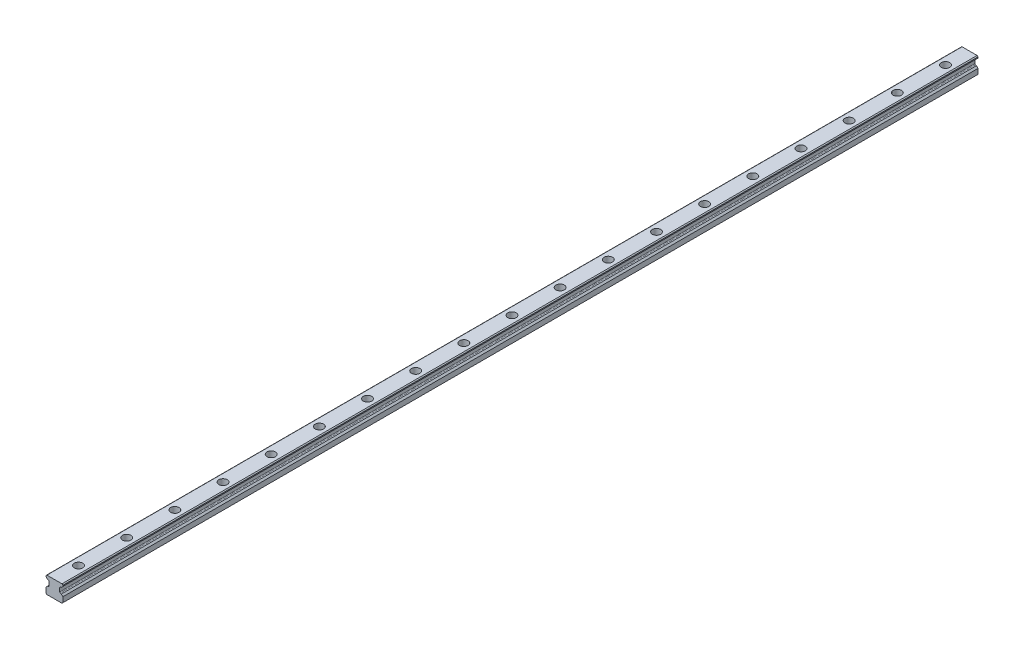
SolidWorks part; units mm, degrees
ref_plane "Front" through (0, 0, 0) normal (0, 0, 1) x (1, 0, 0)
ref_plane "Top" through (0, 0, 0) normal (0, 1, 0) x (1, 0, 0)
ref_plane "Right" through (0, 0, 0) normal (1, 0, 0) x (0, 0, -1)
sketch "Sketch1" plane through (0, 0, 0) normal (0, 0, 1) x (1, 0, 0)
  line L36 (-9.9118, 13.1068) -> (-11.43, 12.7)
  line L37 (-11.43, 12.7) -> (-14, 10.13)
  line L38 (-14, 10.13) -> (-14, 1.5)
  line L39 (-14, 1.5) -> (-12.5, 0)
  line L40 (-12.5, 0) -> (12.5, 0)
  line L41 (12.5, 0) -> (14, 1.5)
  line L42 (14, 1.5) -> (14, 10.13)
  line L43 (14, 10.13) -> (11.43, 12.7)
  line L44 (11.43, 12.7) -> (9.9118, 13.1068)
  line L45 (8.8, 14.5557) -> (8.8, 20.4443)
  line L46 (9.9118, 21.8932) -> (11.43, 22.3)
  line L47 (11.43, 22.3) -> (14, 24.87)
  line L48 (14, 24.87) -> (14, 26.5)
  line L49 (12.5, 28) -> (-12.5, 28)
  line L50 (-14, 26.5) -> (-14, 24.87)
  line L51 (-14, 24.87) -> (-11.43, 22.3)
  line L52 (-11.43, 22.3) -> (-9.9118, 21.8932)
  line L53 (-8.8, 20.4443) -> (-8.8, 14.5557)
  arc A12 (8.8, 14.5557) -> (9.9118, 13.1068) centre (10.3, 14.5557) ccw
  arc A13 (9.9118, 21.8932) -> (8.8, 20.4443) centre (10.3, 20.4443) ccw
  arc A14 (14, 26.5) -> (12.5, 28) centre (11.6492, 25.6492) ccw
  arc A15 (-12.5, 28) -> (-14, 26.5) centre (-11.6492, 25.6492) ccw
  arc A16 (-8.8, 20.4443) -> (-9.9118, 21.8932) centre (-10.3, 20.4443) ccw
  arc A17 (-9.9118, 13.1068) -> (-8.8, 14.5557) centre (-10.3, 14.5557) ccw
extrude "Boss-Extrude1" add sketch "Sketch1" along normal mid plane 1520
sketch "Sketch2" plane through (0, 0, 0) normal (1, 0, 0) x (0, 0, -1)
  line L0 (-720, 28) -> (-720, 0) construction
  line L3 (-720, 28) -> (-713, 28)
  line L4 (-713, 28) -> (-713, 16)
  line L5 (-713, 16) -> (-715.5, 16)
  line L6 (-715.5, 16) -> (-715.5, 0)
  line L7 (-715.5, 0) -> (-720, 0)
  line L8 (-720, 0) -> (-720, 28)
  line L9 (-760, 28) -> (760, 28) construction
  line L10 (-760, 28) -> (-760, 26.5) construction
  line L11 (-760, 0) -> (760, 0) construction
  dimension "D1" = 40
  dimension "D2" = 14
  dimension "D3" = 9
  dimension "D4" = 12
revolve "Cut-Revolve1" cut sketch "Sketch2" angle 360 about L0
pattern_linear "LPattern1" count 2 spacing 80 along (0, 0, -1) of "Cut-Revolve1"
mirror "Mirror1" about plane through (0, 0, 0) normal (0, 0, 1) of "LPattern1", "Cut-Revolve1"
pattern_linear "LPattern2" count 9 spacing 160 along (0, 0, -1) of "LPattern1", "Cut-Revolve1"
sketch "Sketch3" plane through (0, 0, 0) normal (1, 0, 0) x (0, 0, -1)
  line L0 (-713, 28) -> (-713, 16) construction
  line L1 (-713, 16) -> (-715.5, 16) construction
  line L2 (-715.5, 16) -> (-715.5, 0) construction
  line L3 (-720, 28) -> (-713, 28) construction
  line L4 (-715.5, 0) -> (-720, 0) construction
  line L5 (-713, 28) -> (-713, 16)
  line L6 (-713, 16) -> (-715.5, 16)
  line L7 (-715.5, 16) -> (-715.5, 0)
  line L8 (-727, 28) -> (-713, 28)
  line L9 (-715.5, 0) -> (-724.5, 0)
  line L10 (-720, 28) -> (-720, 0) construction
  line L11 (-724.5, 16) -> (-724.5, 0)
  line L12 (-727, 16) -> (-724.5, 16)
  line L13 (-727, 28) -> (-727, 16)
  line L14 (-633, 28) -> (-633, 16)
  line L15 (-633, 16) -> (-635.5, 16)
  line L16 (-635.5, 16) -> (-635.5, 0)
  line L17 (-647, 28) -> (-633, 28)
  line L18 (-635.5, 0) -> (-644.5, 0)
  line L19 (-640, 28) -> (-640, 0) construction
  line L20 (-644.5, 16) -> (-644.5, 0)
  line L21 (-647, 16) -> (-644.5, 16)
  line L22 (-647, 28) -> (-647, 16)
  line L23 (-644.5, 0) -> (-635.5, 0) construction
  line L24 (727, 28) -> (727, 16)
  line L25 (727, 16) -> (724.5, 16)
  line L26 (724.5, 16) -> (724.5, 0)
  line L27 (713, 28) -> (727, 28)
  line L28 (724.5, 0) -> (715.5, 0)
  line L29 (720, 28) -> (720, 0) construction
  line L30 (715.5, 16) -> (715.5, 0)
  line L31 (713, 16) -> (715.5, 16)
  line L32 (713, 28) -> (713, 16)
  line L33 (715.5, 0) -> (724.5, 0) construction
ref_plane "Plane1" [suppressed] through (0, 0, 200) normal (0, 0, 1) x (1, 0, 0)
sketch "Sketch4" [suppressed] plane through (0, 0, 200) normal (0, 0, 1) x (1, 0, 0)
  line L0 (-7, 28) -> (7, 28)
  line L1 (7, 28) -> (-7, 28) construction
  line L2 (12.5, 28) -> (-12.5, 28) construction
  line L3 (7, 28) -> (7, 16)
  line L4 (7, 16) -> (-7, 16) construction
  line L5 (7, 16) -> (4.5, 16)
  line L6 (4.5, 16) -> (-4.5, 16) construction
  line L7 (4.5, 16) -> (4.5, 0)
  line L8 (4.5, 0) -> (-4.5, 0)
  line L9 (-4.5, 0) -> (4.5, 0) construction
  line L10 (0, 0) -> (0, 28) construction
  line L11 (-4.5, 16) -> (-4.5, 0)
  line L12 (-7, 16) -> (-4.5, 16)
  line L13 (-7, 28) -> (-7, 16)
equation "\"D3@LPattern2\"=\"D3@LPattern1\"*2"
